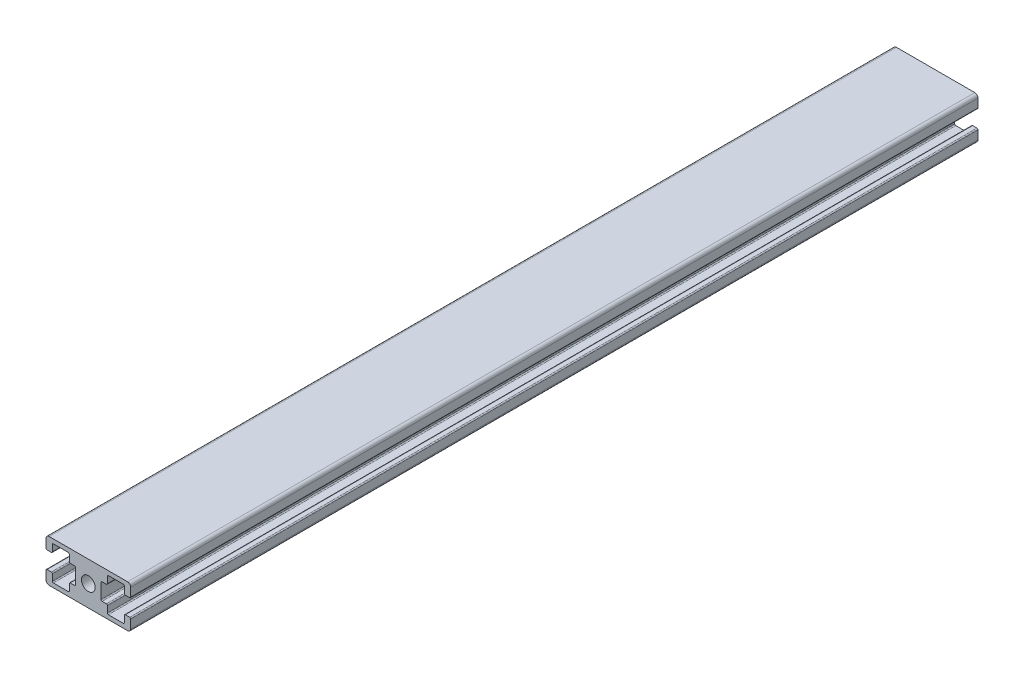
SolidWorks part; units mm, degrees
material "6063-T5"
ref_plane "Front Plane" through (0, 0, 0) normal (0, 0, 1) x (1, 0, 0)
ref_plane "Top Plane" through (0, 0, 0) normal (0, 1, 0) x (1, 0, 0)
ref_plane "Right Plane" through (0, 0, 0) normal (1, 0, 0) x (0, 0, -1)
sketch "Sketch1" plane through (0, 0, 0) normal (0, 0, 1) x (1, 0, 0)
  line L0 (1.5, 0) -> (38.5, 0)
  line L1 (40, 1.5) -> (40, 5.5)
  line L2 (38.5, 20) -> (1.5, 20)
  line L3 (0, 18.5) -> (0, 14.5)
  line L4 (0.5, 14) -> (2.5, 14)
  line L5 (0.5, 6) -> (2.5, 6)
  line L6 (39.5, 14) -> (37.5, 14)
  line L7 (39.5, 6) -> (37.5, 6)
  line L8 (40, 14.5) -> (40, 18.5)
  line L9 (0, 5.5) -> (0, 1.5)
  line L10 (37, 14.5) -> (37, 17.5)
  line L11 (37, 5.5) -> (37, 2.5)
  line L12 (3, 14.5) -> (3, 17.5)
  line L13 (3, 5.5) -> (3, 2.5)
  line L14 (3.5, 18) -> (10.5, 18)
  line L15 (11, 17.5) -> (11, 14.5)
  line L16 (26, 13.5) -> (26, 6.5)
  line L17 (14, 13.5) -> (14, 6.5)
  line L18 (11.5, 14) -> (13.5, 14)
  line L19 (3.5, 2) -> (10.5, 2)
  line L20 (11, 2.5) -> (11, 5.5)
  line L21 (11.5, 6) -> (13.5, 6)
  line L22 (36.5, 18) -> (29.5, 18)
  line L23 (29, 17.5) -> (29, 14.5)
  line L24 (28.5, 14) -> (26.5, 14)
  line L25 (36.5, 2) -> (29.5, 2)
  line L26 (29, 2.5) -> (29, 5.5)
  line L27 (28.5, 6) -> (26.5, 6)
  circle A0 centre (20, 10) radius 3.25
  arc A1 (37, 2.5) -> (36.5, 2) centre (36.5, 2.5) cw
  arc A2 (29.5, 2) -> (29, 2.5) centre (29.5, 2.5) cw
  arc A3 (29, 5.5) -> (28.5, 6) centre (28.5, 5.5) ccw
  arc A4 (26, 6.5) -> (26.5, 6) centre (26.5, 6.5) ccw
  arc A5 (26, 13.5) -> (26.5, 14) centre (26.5, 13.5) cw
  arc A6 (29, 14.5) -> (28.5, 14) centre (28.5, 14.5) cw
  arc A7 (37, 17.5) -> (36.5, 18) centre (36.5, 17.5) ccw
  arc A8 (29.5, 18) -> (29, 17.5) centre (29.5, 17.5) ccw
  arc A9 (10.5, 18) -> (11, 17.5) centre (10.5, 17.5) cw
  arc A10 (11, 14.5) -> (11.5, 14) centre (11.5, 14.5) ccw
  arc A11 (14, 13.5) -> (13.5, 14) centre (13.5, 13.5) ccw
  arc A12 (14, 6.5) -> (13.5, 6) centre (13.5, 6.5) cw
  arc A13 (11, 5.5) -> (11.5, 6) centre (11.5, 5.5) cw
  arc A14 (10.5, 2) -> (11, 2.5) centre (10.5, 2.5) ccw
  arc A15 (3, 2.5) -> (3.5, 2) centre (3.5, 2.5) ccw
  arc A16 (3, 17.5) -> (3.5, 18) centre (3.5, 17.5) cw
  arc A17 (38.5, 0) -> (40, 1.5) centre (38.5, 1.5) ccw
  arc A18 (40, 18.5) -> (38.5, 20) centre (38.5, 18.5) ccw
  arc A19 (1.5, 0) -> (0, 1.5) centre (1.5, 1.5) cw
  arc A20 (1.5, 20) -> (0, 18.5) centre (1.5, 18.5) ccw
  arc A21 (37.5, 6) -> (37, 5.5) centre (37.5, 5.5) ccw
  arc A22 (40, 5.5) -> (39.5, 6) centre (39.5, 5.5) ccw
  arc A23 (37.5, 14) -> (37, 14.5) centre (37.5, 14.5) cw
  arc A24 (40, 14.5) -> (39.5, 14) centre (39.5, 14.5) cw
  arc A25 (0.5, 6) -> (0, 5.5) centre (0.5, 5.5) ccw
  arc A26 (2.5, 6) -> (3, 5.5) centre (2.5, 5.5) cw
  arc A27 (2.5, 14) -> (3, 14.5) centre (2.5, 14.5) ccw
  arc A28 (0.5, 14) -> (0, 14.5) centre (0.5, 14.5) cw
  point P69 (0, 0)
extrude "Boss-Extrude1" add sketch "Sketch1" along normal mid plane 400
